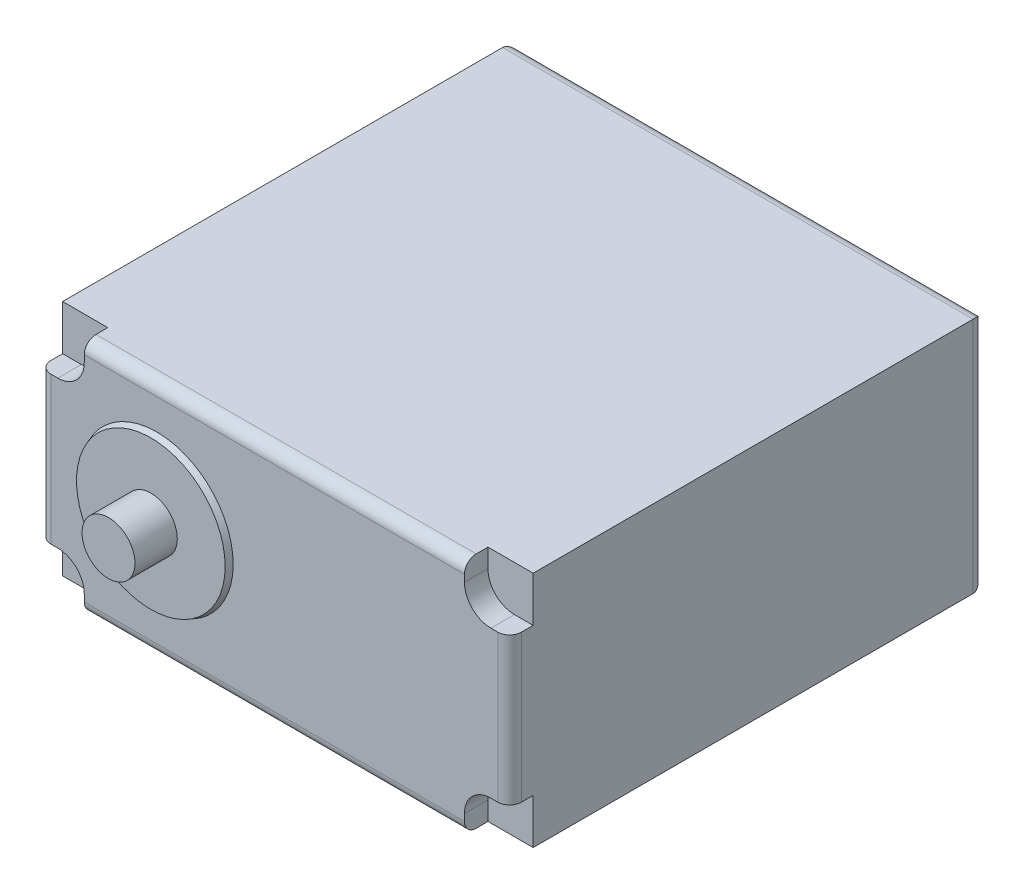
SolidWorks part; units mm, degrees
ref_plane "Front Plane" through (0, 0, 0) normal (0, 0, 1) x (1, 0, 0)
ref_plane "Top Plane" through (0, 0, 0) normal (0, 1, 0) x (1, 0, 0)
ref_plane "Right Plane" through (0, 0, 0) normal (1, 0, 0) x (0, 0, -1)
sketch "Sketch1" plane through (0, 0, 0) normal (0, 1, 0) x (1, 0, 0)
  line L0 (0, 0) -> (40, 0)
  line L1 (40, 0) -> (40, 40.4)
  line L2 (40, 40.4) -> (0, 40.4)
  line L3 (0, 40.4) -> (0, 0)
extrude "Boss-Extrude1" add sketch "Sketch1" along normal blind 20.2
fillet "Fillet1" radius 1 4 edges at (40, 10.1, 0) (0, 10.1, 0) (20, 0, 0) (20, 20.2, 0)
fillet "Fillet2" radius 1 4 edges at (0, 10.1, -40.4) (40, 10.1, -40.4) (20, 0, -40.4) (20, 20.2, -40.4)
sketch "Sketch2" plane through (0, 0, 0) normal (0, 0, 1) x (1, 0, 0)
  line L0 (0, 10.1) -> (40, 10.1) construction
  line L1 (0, 0) -> (0, 20.2) construction
  line L2 (40, 20.2) -> (40, 0) construction
  line L3 (20, 20.2) -> (20, 0) construction
  line L4 (0, 20.2) -> (40, 20.2) construction
  line L5 (40, 0) -> (0, 0) construction
  line L6 (0, 20.2) -> (1.591, 18.609) construction
  line L7 (1.591, 3.841) -> (-0.659, 3.841)
  line L8 (-0.659, 3.841) -> (-0.659, 1.591)
  line L9 (3.841, 1.591) -> (3.841, -0.5577)
  line L10 (3.841, -0.5577) -> (1.591, -0.659)
  line L11 (3.841, 18.609) -> (3.841, 20.859)
  line L12 (3.841, 20.859) -> (1.591, 20.859)
  line L13 (1.591, 16.359) -> (-0.659, 16.359)
  line L14 (-0.659, 16.359) -> (-0.659, 18.609)
  line L15 (36.159, -0.5577) -> (38.409, -0.659)
  line L16 (36.159, 1.591) -> (36.159, -0.5577)
  line L17 (38.409, 3.841) -> (40.659, 3.841)
  line L18 (40.659, 3.841) -> (40.659, 1.591)
  line L19 (36.159, 18.609) -> (36.159, 20.859)
  line L20 (36.159, 20.859) -> (38.409, 20.859)
  line L21 (40.659, 16.359) -> (40.659, 18.609)
  line L22 (38.409, 16.359) -> (40.659, 16.359)
  arc A0 (1.591, 16.359) -> (3.841, 18.609) centre (1.591, 18.609) ccw
  arc A3 (1.591, 3.841) -> (3.841, 1.591) centre (1.591, 1.591) cw
  arc A4 (1.591, -0.659) -> (-0.659, 1.591) centre (1.591, 1.591) cw
  arc A5 (1.591, 20.859) -> (-0.659, 18.609) centre (1.591, 18.609) ccw
  arc A6 (38.409, 3.841) -> (36.159, 1.591) centre (38.409, 1.591) ccw
  arc A7 (38.409, -0.659) -> (40.659, 1.591) centre (38.409, 1.591) ccw
  arc A8 (38.409, 16.359) -> (36.159, 18.609) centre (38.409, 18.609) cw
  arc A9 (38.409, 20.859) -> (40.659, 18.609) centre (38.409, 18.609) cw
extrude "Cut-Extrude1" cut sketch "Sketch2" against normal blind 2
sketch "Sketch3" plane through (0, 0, 0) normal (0, 0, 1) x (1, 0, 0)
  line L0 (0, 10.1) -> (40, 10.1) construction
  line L1 (0, 3.841) -> (0, 16.359) construction
  line L2 (40, 16.359) -> (40, 3.841) construction
  line L3 (20, 20.2) -> (20, 0) construction
  line L4 (3.841, 20.2) -> (36.159, 20.2) construction
  line L5 (36.159, 0) -> (3.841, 0) construction
  line L6 (0, 10.1) -> (10, 10.1) construction
  circle A0 centre (10, 10.1) radius 6.5
extrude "Boss-Extrude2" add sketch "Sketch3" along normal blind 0.5 draft 20
sketch "Sketch4" plane through (0, 0, 0.5) normal (0, 0, 1) x (1, 0, 0)
  circle A0 centre (10, 10.1) radius 2.25
extrude "Boss-Extrude3" add sketch "Sketch4" along normal blind 3.6
ref_plane "Plane1" through (0, 0, -20.2) normal (0, 0, -1) x (-1, 0, 0)
mirror "Mirror2" about plane through (0, 0, -20.2) normal (0, 0, -1) of "Boss-Extrude3", "Boss-Extrude2"
